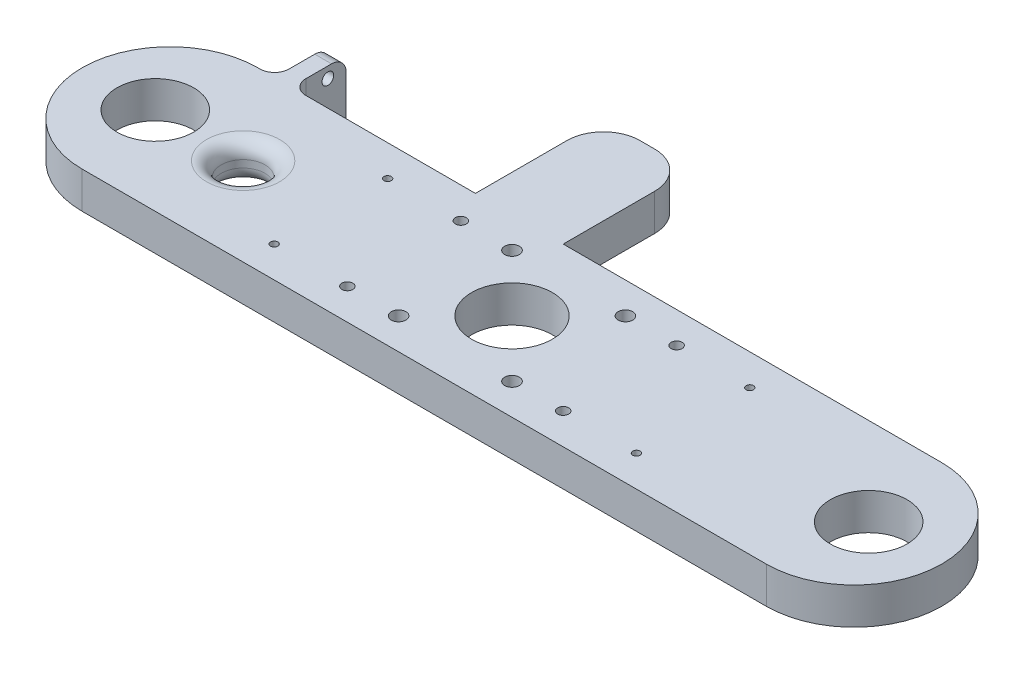
SolidWorks part; units mm, degrees
ref_plane "Front Plane" through (0, 0, 0) normal (0, 0, 1) x (1, 0, 0)
ref_plane "Top Plane" through (0, 0, 0) normal (0, 1, 0) x (1, 0, 0)
ref_plane "Right Plane" through (0, 0, 0) normal (1, 0, 0) x (0, 0, -1)
sketch "Sketch1" plane through (0, 0, 0) normal (0, 1, 0) x (1, 0, 0)
  line L0 (-93.5, 0) -> (93.5, 0) construction
  line L1 (-93.5, 24) -> (93.5, 24)
  line L2 (-93.5, -24) -> (93.5, -24)
  line L3 (0, 0) -> (0, 24) construction
  line L4 (-10, 24) -> (-10, 49)
  line L5 (-34, 24) -> (-34, 49)
  line L6 (-10, 49) -> (-20, 49) construction
  line L7 (-34, 49) -> (-24, 49) construction
  line L8 (-20, 59) -> (-24, 59)
  line L9 (-34, 24) -> (-10, 24)
  arc A0 (-93.5, 24) -> (-93.5, -24) centre (-93.5, 0) ccw
  arc A1 (93.5, -24) -> (93.5, 24) centre (93.5, 0) ccw
  arc A2 (-10, 49) -> (-20, 59) centre (-20, 49) ccw
  arc A3 (-34, 49) -> (-24, 59) centre (-24, 49) cw
  point P2 (0, 0)
  dimension "D1" = 24
  dimension "D2" = 187
  dimension "D3" = 10
  dimension "D4" = 25
  dimension "D5" = 25
  dimension "D6" = 24
  dimension "D7" = 10
  dimension "D8" = 10
extrude "Boss-Extrude1" add sketch "Sketch1" along normal blind 10 contours A3 L5 L1 L4 A2 L8 | L2 A1 L1 A0
sketch "Sketch2" plane through (0, 10, 0) normal (0, 1, 0) x (1, 0, 0)
  line L2 (0, 0) -> (0, 24) construction
  line L3 (-10, 24) -> (93.5, 24) construction
  line L4 (0, 0) -> (-28.1945, 0) construction
  line L6 (-15.5, 15.5) -> (15.5, 15.5) construction
  line L8 (-15.5, 15.5) -> (-15.5, -15.5) construction
  line L9 (15.5, 15.5) -> (15.5, -15.5) construction
  line L10 (-15.5, -15.5) -> (15.5, -15.5) construction
  line L11 (-15.5, -15.5) -> (15.5, 15.5) construction
  line L12 (-15.5, 15.5) -> (15.5, -15.5) construction
  circle A0 centre (-97.5, 0) radius 10.5
  arc A1 (-93.5, 24) -> (-93.5, -24) centre (-93.5, 0) ccw construction
  circle A2 centre (97.5, 0) radius 10.5
  arc A3 (93.5, -24) -> (93.5, 24) centre (93.5, 0) ccw construction
  circle A4 centre (-73.5, 0) radius 6
  circle A15 centre (0, 0) radius 11.05
  circle A16 centre (-15.5, 15.5) radius 2
  circle A17 centre (15.5, 15.5) radius 2
  circle A18 centre (-15.5, -15.5) radius 2
  circle A19 centre (15.5, -15.5) radius 2
  circle A20 centre (29.5, 15.5) radius 1.5
  circle A21 centre (29.5, -15.5) radius 1.5
  circle A22 centre (-29.5, 15.5) radius 1.5
  circle A23 centre (-29.5, -15.5) radius 1.5
  circle A24 centre (-49.5, 15.5) radius 1
  circle A25 centre (-49.5, -15.5) radius 1
  circle A26 centre (49.5, 15.5) radius 1
  circle A27 centre (49.5, -15.5) radius 1
  point P5 (-117.5, 0)
  point P11 (117.5, 0)
  dimension "D1" = 20
  dimension "D2" = 21
  dimension "D3" = 20
  dimension "D4" = 21
  dimension "D5" = 12
  dimension "D6" = 24
  dimension "D7" = 22.1
  dimension "D10" = 15.5
  dimension "D11" = 31
  dimension "D12" = 4
  dimension "D13" = 31
  dimension "D14" = 4
  dimension "D15" = 4
  dimension "D16" = 3
  dimension "D17" = 14
  dimension "D18" = 3
  dimension "D19" = 3
  dimension "D20" = 14
  dimension "D22" = 14
  dimension "D23" = 2
  dimension "D25" = 2
  dimension "D8" = 4
  dimension "D24" = 20
  dimension "D9" = 15.5
  dimension "D21" = 3
  dimension "D26" = 2
  dimension "D27" = 20
  dimension "D28" = 2
extrude "Cut-Extrude1" cut sketch "Sketch2" against normal blind 10
fillet "Fillet1" radius 4 1 edges at (-73.5, 10, 6)
fillet "Fillet2" radius 4 1 edges at (-73.5, 0, 6)
sketch "Sketch3" plane through (0, 0, -24) normal (0, 0, -1) x (-1, 0, 0)
  line L0 (93.5, 10) -> (34, 10) construction
  line L1 (84.33, 10) -> (88.91, 10)
  line L2 (84.33, 10) -> (84.33, -10)
  line L3 (84.33, -10) -> (88.91, -10)
  line L4 (88.91, 10) -> (88.91, -10)
  line L5 (34, 10) -> (34, 0) construction
  dimension "D1" = 4.58
  dimension "D2" = 50.33
  dimension "D3" = 20
extrude "Boss-Extrude2" add sketch "Sketch3" along normal blind 15
fillet "Fillet3" radius 4 1 edges at (-86.62, 0, -24)
fillet "Fillet4" radius 4 2 edges at (-84.33, 5, -24) (-88.91, 5, -24)
fillet "Fillet5" radius 4 3 edges at (-86.62, 10, -39) (-86.62, -10, -39) (-86.62, -10, -24)
sketch "Sketch4" plane through (-88.91, 0, 0) normal (-1, 0, 0) x (0, 0, 1)
  line L0 (-35, -10) -> (-28, -10) construction
  line L1 (-35, 10) -> (-28, 10) construction
  line L2 (-39, -6) -> (-39, 6) construction
  circle A0 centre (-34, 7) radius 1.6
  circle A1 centre (-34, -7) radius 1.6
  dimension "D1" = 14
  dimension "D2" = 3.2
  dimension "D3" = 3.2
  dimension "D5" = 3
  dimension "D6" = 5
  dimension "D4" = 20
extrude "Cut-Extrude2" cut sketch "Sketch4" against normal blind 15
